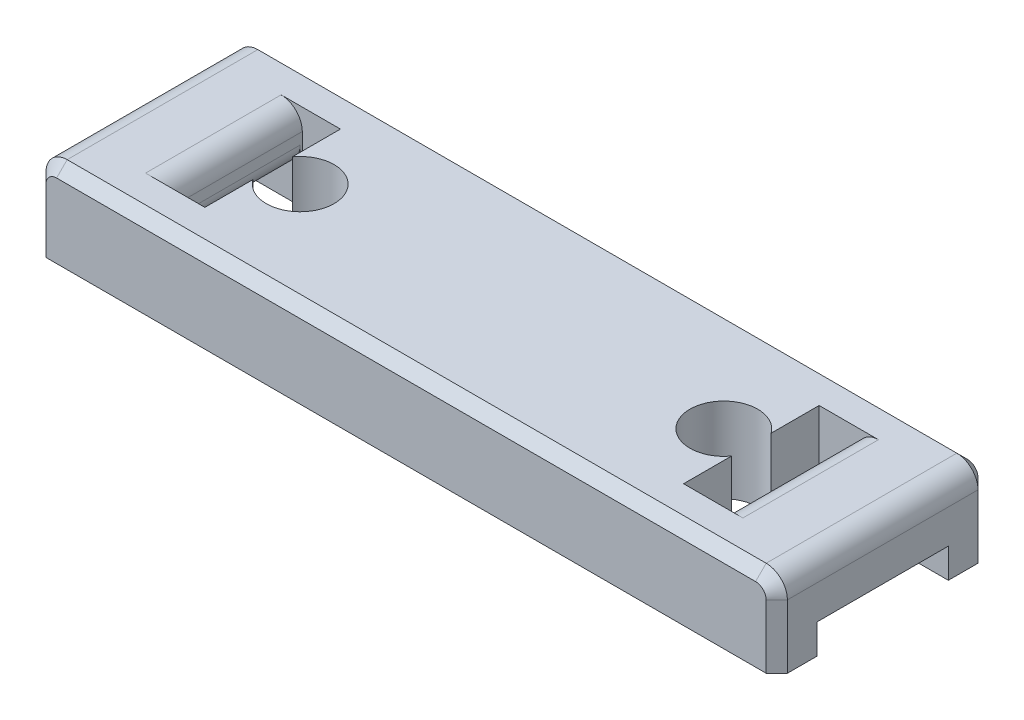
SolidWorks part; units mm, degrees
ref_plane "Front Plane" through (0, 0, 0) normal (0, 0, 1) x (1, 0, 0)
ref_plane "Top Plane" through (0, 0, 0) normal (0, 1, 0) x (1, 0, 0)
ref_plane "Right Plane" through (0, 0, 0) normal (1, 0, 0) x (0, 0, -1)
sketch "Sketch2" plane through (0, 0, 0) normal (0, 1, 0) x (1, 0, 0)
  line L1 (-17.5, -5) -> (17.5, -5)
  line L2 (-17.5, -5) -> (-17.5, 5)
  line L3 (-17.5, 5) -> (17.5, 5)
  line L4 (17.5, -5) -> (17.5, 5)
  line L5 (-17.5, -5) -> (17.5, 5) construction
  line L6 (-17.5, 5) -> (17.5, -5) construction
  point P0 (0, 0)
  dimension "D1" = 35
  dimension "D2" = 10
extrude "Boss-Extrude1" add sketch "Sketch2" along normal blind 4
sketch "Sketch3" plane through (0, 4, 0) normal (0, 1, 0) x (1, 0, 0)
  line L0 (0, 5) -> (0, -5) construction
  line L1 (17.5, 5) -> (-17.5, 5) construction
  line L2 (-17.5, -5) -> (17.5, -5) construction
  line L3 (-17.5, 0) -> (17.5, 0) construction
  line L4 (-17.5, 5) -> (-17.5, -5) construction
  line L5 (17.5, -5) -> (17.5, 5) construction
  line L6 (-11.3, 0.9327) -> (-11.3, 3.2)
  line L7 (-13.1, -3.2) -> (-11.3, -3.2)
  line L8 (-13.1, -3.2) -> (-13.1, 3.2)
  line L9 (-13.1, 3.2) -> (-11.3, 3.2)
  line L10 (-11.3, -3.2) -> (-11.3, -0.9327)
  line L11 (-13.1, -3.2) -> (-11.3, 3.2) construction
  line L12 (-13.1, 3.2) -> (-11.3, -3.2) construction
  line L13 (11.3, -3.2) -> (11.3, -0.9327)
  line L14 (13.1, -3.2) -> (11.3, -3.2)
  line L15 (13.1, -3.2) -> (13.1, 3.2)
  line L16 (13.1, 3.2) -> (11.3, 3.2)
  line L17 (11.3, 0.9327) -> (11.3, 3.2)
  arc A0 (-11.3, -0.9327) -> (-11.3, 0.9327) centre (-10, 0) ccw
  arc A1 (11.3, -0.9327) -> (11.3, 0.9327) centre (10, 0) cw
  point P14 (-12.2, 0)
  point P19 (-11.6, 0)
  dimension "D1" = 3.2
  dimension "D2" = 20
  dimension "D3" = 2.2
  dimension "D4" = 6.4
  dimension "D5" = 1.8
extrude "Cut-Extrude1" cut sketch "Sketch3" against normal up to surface (4 mm away) up to face at (0, 0, 0)
sketch "Sketch4" plane through (-17.5, 0, 0) normal (-1, 0, 0) x (0, 0, 1)
  line L0 (0, 4) -> (0, 0) construction
  line L1 (-5, 4) -> (5, 4) construction
  line L2 (-3.1, 0) -> (-3.1, 1.5)
  line L3 (-5, 0) -> (5, 0) construction
  line L4 (-3.1, 1.5) -> (3.1, 1.5)
  line L5 (-3.1, 0) -> (3.1, 0)
  line L6 (3.1, 0) -> (3.1, 1.5)
  point P11 (0, 1.5)
  dimension "D1" = 1.5
  dimension "D2" = 6.2
extrude "Cut-Extrude2" cut sketch "Sketch4" against normal up to surface (4.4 mm away) up to face at (-13.1, 2, 0)
sketch "Sketch5" plane through (17.5, 0, 0) normal (1, 0, 0) x (0, 0, -1)
  line L0 (0, 4) -> (0, 0) construction
  line L1 (-5, 4) -> (5, 4) construction
  line L2 (-5, 0) -> (5, 0) construction
  line L3 (3.1, 0) -> (-3.1, 0)
  line L4 (-3.1, 0) -> (-3.1, 1.4)
  line L5 (-3.1, 1.4) -> (3.1, 1.4)
  line L6 (3.1, 0) -> (3.1, 1.4)
  point P10 (0, 1.4)
  dimension "D1" = 1.4
  dimension "D2" = 6.2
extrude "Cut-Extrude3" cut sketch "Sketch5" against normal up to surface (4.4 mm away) up to face at (13.1, 2, 0)
fillet "Fillet1" radius 1 4 edges at (-13.1, 1.5, 0) (13.1, 4, 0) (-13.1, 4, 0) (13.1, 1.4, 0)
fillet "Fillet2" radius 1 2 edges at (-17.5, 4, 0) (17.5, 4, 0)
chamfer "Chamfer1" distance 0.5 angle 45 10 edges at (17.5, 1.5, -5) (-17.5, 1.5, -5) (17.2071, 3.7071, -5) (-17.2071, 3.7071, -5) (0, 4, -5) (17.5, 1.5, 5) (17.2071, 3.7071, 5) (0, 4, 5) (-17.2071, 3.7071, 5) (-17.5, 1.5, 5)
